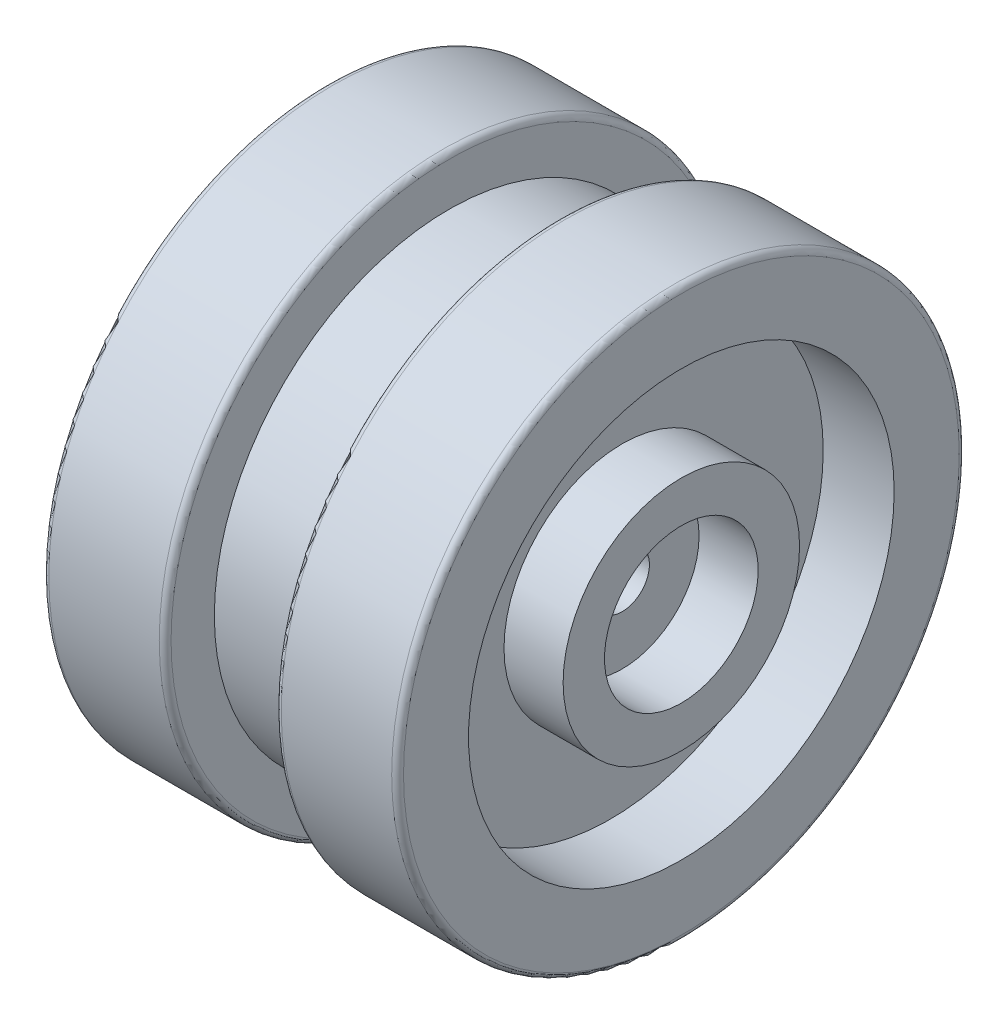
SolidWorks part; units mm, degrees
ref_plane "Front Plane" through (0, 0, 0) normal (0, 0, 1) x (1, 0, 0)
ref_plane "Top Plane" through (0, 0, 0) normal (0, 1, 0) x (1, 0, 0)
ref_plane "Right Plane" through (0, 0, 0) normal (1, 0, 0) x (0, 0, -1)
sketch "Sketch2" plane through (0, 0, 0) normal (0, 0, 1) x (1, 0, 0)
  line L0 (-2.0852, 1.3557) -> (7.2348, 1.3557)
  line L1 (-2.0852, 1.3557) -> (-2.0852, 5.5157)
  line L2 (7.2348, 1.3557) -> (7.2348, 5.5157)
  line L3 (7.2348, 5.5157) -> (17.5748, 5.5157)
  line L4 (-2.0852, 5.5157) -> (-12.4252, 5.5157)
  line L5 (-12.4252, 5.5157) -> (-12.4252, -18.4843)
  line L6 (-12.4252, -18.4843) -> (17.5748, -18.4843)
  line L7 (17.5748, -18.4843) -> (17.5748, 5.5157)
  line L8 (-12.4252, -18.4843) -> (27.3603, -18.4843) construction
  dimension "D1" = 30
  dimension "D2" = 24
  dimension "D4" = 4.16
  dimension "D5" = 9.32
revolve "Revolve1" add sketch "Sketch2" angle 360 about L8
sketch "Sketch3" plane through (17.5748, 0, 0) normal (1, 0, 0) x (0, 0, -1)
  circle A0 centre (0, -18.4843) radius 2
extrude "Cut-Extrude1" cut sketch "Sketch3" against normal through all
fillet "Fillet2" radius 0.5 4 edges at (-2.0852, -18.4843, 24) (7.2348, -18.4843, 24) (17.5748, -18.4843, 24) (-12.4252, -18.4843, 24)
sketch "Sketch4" plane through (17.5748, 0, 0) normal (1, 0, 0) x (0, 0, -1)
  circle A0 centre (0, -18.4843) radius 6
  circle A1 centre (0, -18.4843) radius 18
extrude "Cut-Extrude2" cut sketch "Sketch4" against normal blind 6
sketch "Sketch5" plane through (-12.4252, 0, 0) normal (-1, 0, 0) x (0, 0, 1)
  circle A0 centre (0, -18.4843) radius 6
  circle A1 centre (0, -18.4843) radius 18
extrude "Cut-Extrude3" cut sketch "Sketch5" against normal blind 6 contours A1
sketch "Sketch6" plane through (-6.4252, 0, 0) normal (-1, 0, 0) x (0, 0, 1)
  circle A0 centre (0, -18.4843) radius 10
extrude "Boss-Extrude1" add sketch "Sketch6" along normal through all
sketch "Sketch7" plane through (-12.4252, 0, 0) normal (-1, 0, 0) x (0, 0, 1)
  circle A0 centre (0, -18.4843) radius 2.3
  dimension "D1" = 4.6
sketch "Sketch8" plane through (17.5748, 0, 0) normal (1, 0, 0) x (0, 0, -1)
  circle A0 centre (0, -18.4843) radius 8
extrude "Boss-Extrude2" add sketch "Sketch8" against normal blind 10 contours A0
sketch "Sketch9" plane through (17.5748, 0, 0) normal (1, 0, 0) x (0, 0, -1)
  circle A0 centre (0, -18.4843) radius 6.5
sketch "Sketch10" plane through (-12.4252, 0, 0) normal (-1, 0, 0) x (0, 0, 1)
  circle A0 centre (0, -18.4843) radius 6.5
extrude "Cut-Extrude5" cut sketch "Sketch10" against normal blind 5 contours A0
sketch "Sketch11" plane through (17.5748, 0, 0) normal (1, 0, 0) x (0, 0, -1)
  circle A0 centre (0, -18.4843) radius 10
extrude "Boss-Extrude3" add sketch "Sketch11" against normal blind 5
sketch "Sketch12" plane through (17.5748, 0, 0) normal (1, 0, 0) x (0, 0, -1)
  circle A0 centre (0, -18.4843) radius 6.5
extrude "Cut-Extrude6" cut sketch "Sketch12" against normal blind 5
extrude "Cut-Extrude8" cut sketch "Sketch7" against normal through all contours A0
ref_plane "Plane1" through (0, 0, -19.84) normal (0, 0, -1) x (-1, 0, 0)
sketch "Sketch13" plane through (0, 0, -19.84) normal (0, 0, -1) x (-1, 0, 0)
  line L0 (2.0852, 1.3557) -> (2.0852, -38.3243) construction
  line L1 (-7.2348, -38.3243) -> (-7.2348, 1.3557) construction
  line L2 (2.0852, 1.3557) -> (2.0852, -38.3243)
  line L3 (-7.2348, -38.3243) -> (-7.2348, 1.3557)
  line L4 (-2.5748, 1.3557) -> (-2.5748, -38.3243) construction
  dimension "D1" = 4.66
